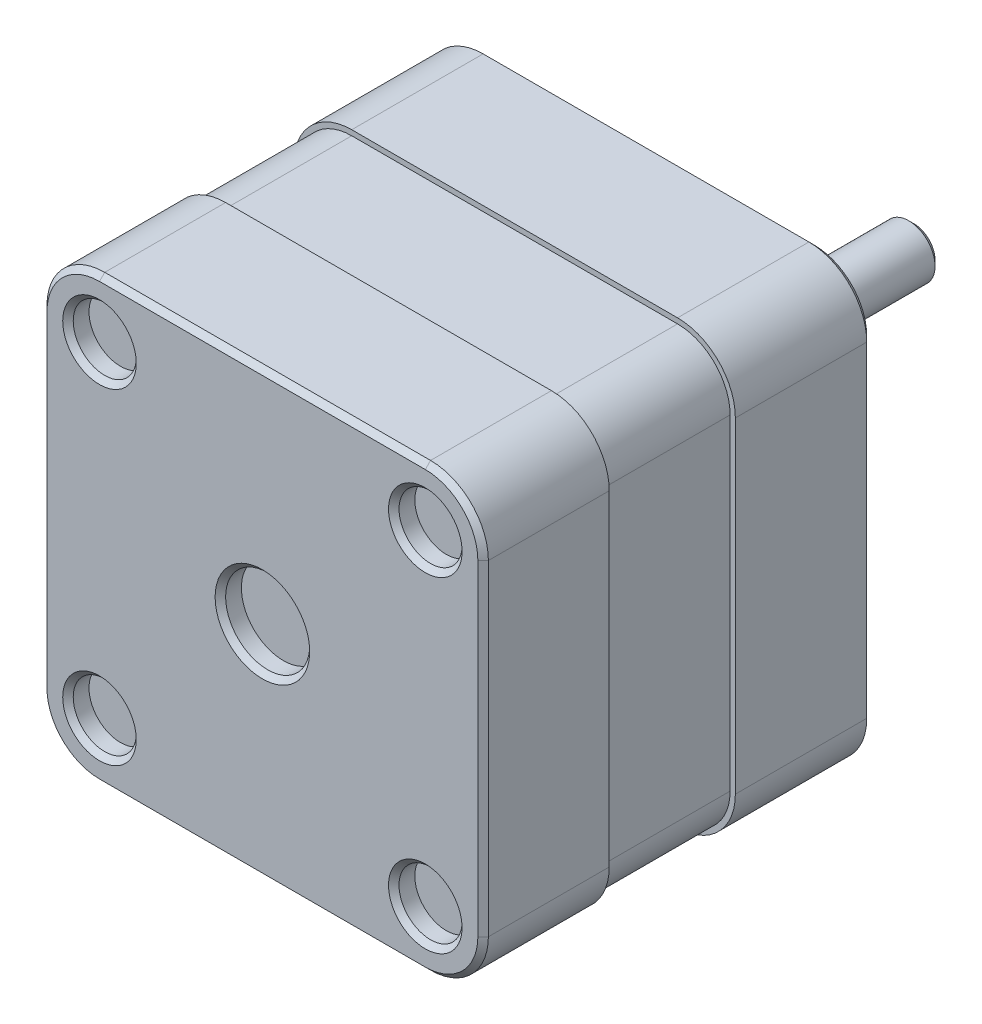
SolidWorks part; units mm, degrees
ref_plane "Front Plane" through (0, 0, 0) normal (0, 0, 1) x (1, 0, 0)
ref_plane "Top Plane" through (0, 0, 0) normal (0, 1, 0) x (1, 0, 0)
ref_plane "Right Plane" through (0, 0, 0) normal (1, 0, 0) x (0, 0, -1)
sketch "Sketch1" plane through (0, 0, 0) normal (0, 0, 1) x (1, 0, 0)
  line L1 (-21, -21) -> (21, -21)
  line L2 (-21, -21) -> (-21, 21)
  line L3 (-21, 21) -> (21, 21)
  line L4 (21, -21) -> (21, 21)
  line L5 (-21, -21) -> (21, 21) construction
  line L6 (-21, 21) -> (21, -21) construction
  point P0 (0, 0)
  dimension "D1" = 42
  dimension "D2" = 42
extrude "Boss-Extrude1" add sketch "Sketch1" along normal blind 37
fillet "Fillet1" radius 5.5 4 edges at (-21, -21, 18.5) (21, -21, 18.5) (21, 21, 18.5) (-21, 21, 18.5)
sketch "Sketch2" plane through (0, 0, 37) normal (0, 0, 1) x (1, 0, 0)
  circle A0 centre (0, 0) radius 4
  circle A1 centre (15.5, -15.5) radius 3
  circle A2 centre (15.5, 15.5) radius 3
  circle A3 centre (-15.5, 15.5) radius 3
  circle A4 centre (-15.5, -15.5) radius 3
  dimension "D1" = 8
  dimension "D2" = 6
extrude "Cut-Extrude1" cut sketch "Sketch2" against normal blind 2
sketch "Sketch4" plane through (0, 0, 0) normal (0, 0, -1) x (-1, 0, 0)
  circle A0 centre (0, 0) radius 2.5
  dimension "D1" = 5
extrude "Boss-Extrude2" add sketch "Sketch4" along normal blind 25
sketch "Sketch5" plane through (0, 0, 0) normal (0, 0, -1) x (-1, 0, 0)
  circle A0 centre (15.5, -15.5) radius 1.5
  circle A1 centre (-15.5, -15.5) radius 1.5
  circle A2 centre (15.5, 15.5) radius 1.5
  circle A3 centre (-15.5, 15.5) radius 1.5
  dimension "D1" = 3
extrude "Cut-Extrude2" cut sketch "Sketch5" against normal blind 8
sketch "Sketch6" plane through (0, 0, 37) normal (0, 0, 1) x (1, 0, 0)
  line L0 (-15.5, -21) -> (15.5, -21) construction
  line L1 (21, -15.5) -> (21, 15.5) construction
  line L2 (-21, 15.5) -> (-21, -15.5) construction
  line L3 (15.5, 21) -> (-15.5, 21) construction
  line L4 (-15.5, -21) -> (15.5, -21)
  line L5 (21, -15.5) -> (21, 15.5)
  line L6 (-21, 15.5) -> (-21, -15.5)
  line L7 (15.5, 21) -> (-15.5, 21)
  line L8 (-20.5, 15.5) -> (-20.5, -15.5)
  line L9 (-15.5, -20.5) -> (15.5, -20.5)
  line L10 (20.5, -15.5) -> (20.5, 15.5)
  line L11 (15.5, 20.5) -> (-15.5, 20.5)
  arc A0 (-21, -15.5) -> (-15.5, -21) centre (-15.5, -15.5) ccw construction
  arc A1 (15.5, -21) -> (21, -15.5) centre (15.5, -15.5) ccw construction
  arc A2 (21, 15.5) -> (15.5, 21) centre (15.5, 15.5) ccw construction
  arc A3 (-15.5, 21) -> (-21, 15.5) centre (-15.5, 15.5) ccw construction
  arc A4 (-21, -15.5) -> (-15.5, -21) centre (-15.5, -15.5) ccw
  arc A5 (15.5, -21) -> (21, -15.5) centre (15.5, -15.5) ccw
  arc A6 (21, 15.5) -> (15.5, 21) centre (15.5, 15.5) ccw
  arc A7 (-15.5, 21) -> (-21, 15.5) centre (-15.5, 15.5) ccw
  circle A8 centre (0, 0) radius 34.3084
  arc A9 (-20.5, -15.5) -> (-15.5, -20.5) centre (-15.5, -15.5) ccw
  arc A10 (15.5, -20.5) -> (20.5, -15.5) centre (15.5, -15.5) ccw
  arc A11 (20.5, 15.5) -> (15.5, 20.5) centre (15.5, 15.5) ccw
  arc A12 (-15.5, 20.5) -> (-20.5, 15.5) centre (-15.5, 15.5) ccw
  line M6 (-21, 15.5) -> (-21, -15.5)
  arc M7 (-21, -15.5) -> (-15.5, -21) centre (-15.5, -15.5) ccw
  line M8 (-15.5, -21) -> (15.5, -21)
  arc M9 (15.5, -21) -> (21, -15.5) centre (15.5, -15.5) ccw
  line M10 (21, -15.5) -> (21, 15.5)
  arc M11 (21, 15.5) -> (15.5, 21) centre (15.5, 15.5) ccw
  line M12 (15.5, 21) -> (-15.5, 21)
  arc M13 (-15.5, 21) -> (-21, 15.5) centre (-15.5, 15.5) ccw
  dimension "D1" = 0.5
extrude "Cut-Extrude3" cut sketch "Sketch6" against normal blind 12 from offset 12 contours A8 M6 M13 M12 M11 M10 M9 M8 M7 | A12 L11 A11 L10 A10 L9 A9 L8 M13 M6 M7 M8 M9 M10 M11 M12 offset against normal yes
chamfer "Chamfer1" distance 0.5 angle 45 27 edges at (-19.3891, 19.3891, 37) (0, 21, 37) (19.3891, 19.3891, 37) (21, 0, 37) (19.3891, -19.3891, 37) (0, -21, 37) (-19.3891, -19.3891, 37) (-21, 0, 37) (4, 0, 37) (-12.5, -15.5, 37) (-12.5, 15.5, 37) (18.5, 15.5, 37) (18.5, -15.5, 37) (-2.5, 0, -25) (19.3891, -19.3891, 0) (21, 0, 0) (19.3891, 19.3891, 0) (0, 21, 0) (-19.3891, 19.3891, 0) (-21, 0, 0) (-19.3891, -19.3891, 0) (0, -21, 0) (-2.5, 0, 0) (-17, -15.5, 0) (14, 15.5, 0) (-17, 15.5, 0) (14, -15.5, 0)
sketch "Sketch7" plane through (0, 0, 0) normal (0, 0, -1) x (-1, 0, 0)
  circle A0 centre (0, 0) radius 11
  dimension "D1" = 22
extrude "Boss-Extrude3" add sketch "Sketch7" along normal blind 1
